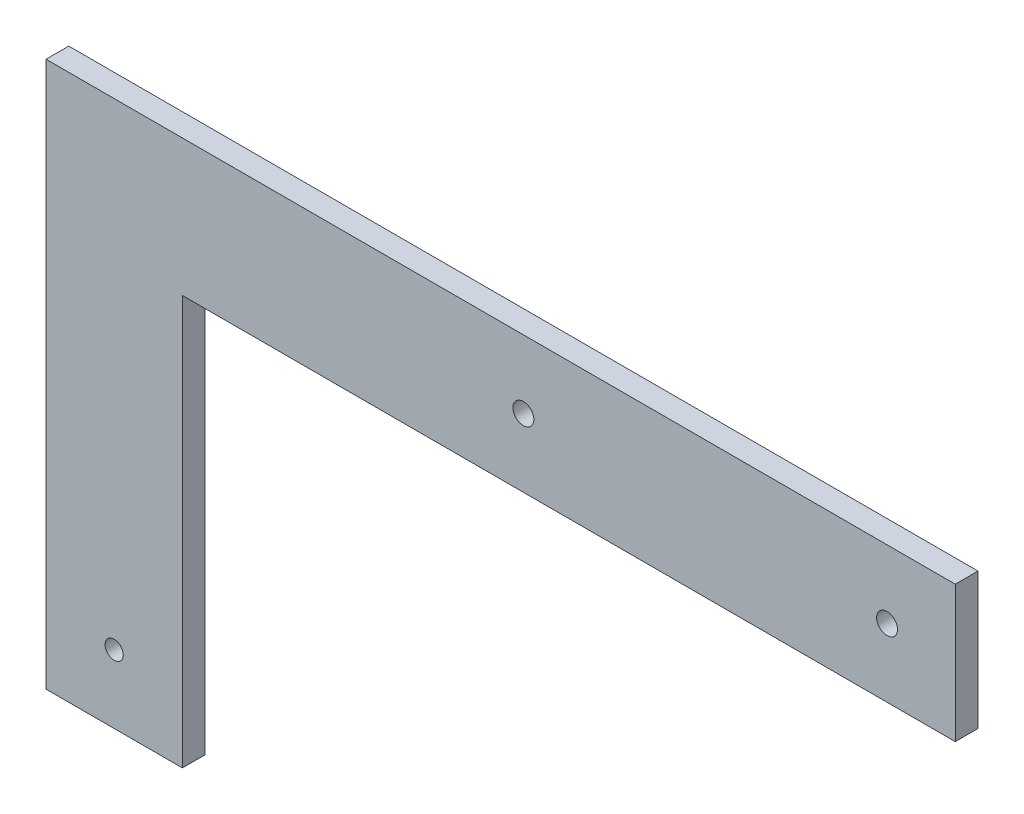
SolidWorks part; units mm, degrees
ref_plane "Front Plane" through (0, 0, 0) normal (0, 0, 1) x (1, 0, 0)
ref_plane "Top Plane" through (0, 0, 0) normal (0, 1, 0) x (1, 0, 0)
ref_plane "Right Plane" through (0, 0, 0) normal (1, 0, 0) x (0, 0, -1)
sketch "Sketch1" plane through (0, 0, 0) normal (0, 0, 1) x (1, 0, 0)
  line L0 (0, 0) -> (0, 76.2)
  line L1 (0, 76.2) -> (127, 76.2)
  line L2 (127, 76.2) -> (127, 57.15)
  line L3 (127, 57.15) -> (19.05, 57.15)
  line L4 (19.05, 57.15) -> (19.05, 0)
  line L5 (19.05, 0) -> (0, 0)
  dimension "D1" = 76.2
  dimension "D2" = 127
  dimension "D3" = 19.05
  dimension "D4" = 19.05
extrude "Boss-Extrude1" add sketch "Sketch1" along normal blind 3.175
sketch "Sketch2" plane through (0, 0, 3.175) normal (0, 0, 1) x (1, 0, 0)
  line L0 (127, 57.15) -> (127, 76.2) construction
  line L1 (0, 0) -> (19.05, 0) construction
  circle A0 centre (9.525, 9.525) radius 1.27
  circle A1 centre (117.475, 66.675) radius 1.4605
  circle A2 centre (66.675, 66.675) radius 1.4605
  dimension "D1" = 50.8
  dimension "D2" = 9.525
  dimension "D3" = 2.921
  dimension "D4" = 2.921
  dimension "D5" = 2.54
  dimension "D6" = 9.525
extrude "Cut-Extrude1" cut sketch "Sketch2" against normal through all
